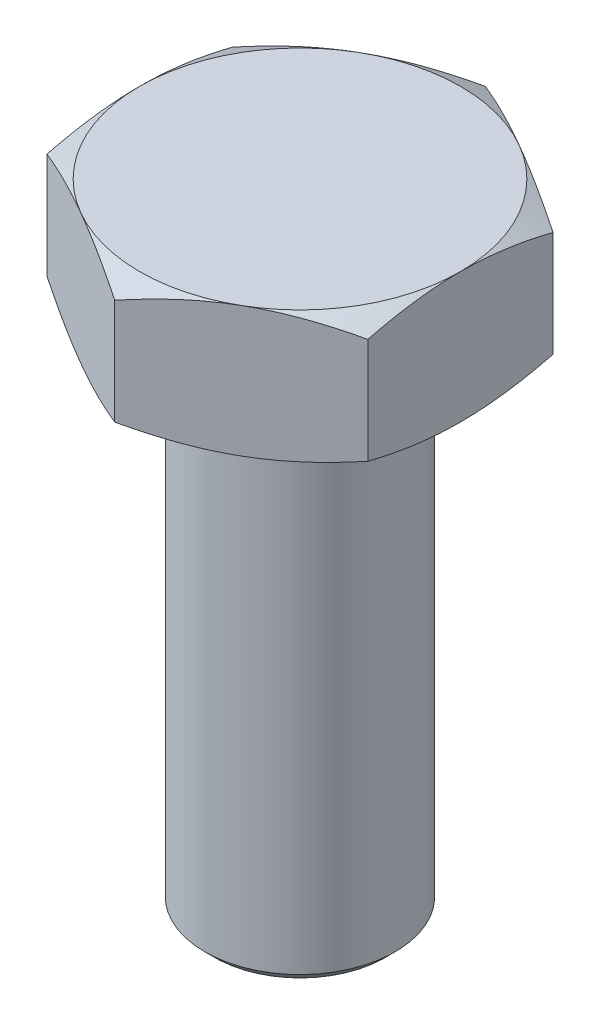
SolidWorks part; units mm, degrees
ref_plane "Front" through (0, 0, 0) normal (0, 0, 1) x (1, 0, 0)
ref_plane "Top" through (0, 0, 0) normal (0, 1, 0) x (1, 0, 0)
ref_plane "Right" through (0, 0, 0) normal (1, 0, 0) x (0, 0, -1)
sketch "Sketch1" plane through (0, 0, 0) normal (0, 1, 0) x (1, 0, 0)
  line L0 (0, 0) -> (0, 9.2376) construction
  line L1 (0, 9.2376) -> (-8, 4.6188)
  line L2 (-8, 4.6188) -> (-8, -4.6188)
  line L3 (-8, -4.6188) -> (0, -9.2376)
  line L4 (0, -9.2376) -> (8, -4.6188)
  line L5 (8, -4.6188) -> (8, 4.6188)
  line L6 (8, 4.6188) -> (0, 9.2376)
  circle A0 centre (0, 0) radius 8 construction
  dimension "D1" = 16
extrude "Boss-Extrude1" add sketch "Sketch1" against normal blind 6.5
sketch "Sketch2" plane through (0, 0, 0) normal (0, 0, 1) x (1, 0, 0)
  line L0 (-11, -1.5) -> (-8, 0)
  line L1 (-8, 0) -> (-8, 1)
  line L2 (-8, 1) -> (-11, 1)
  line L3 (-11, 1) -> (-11, -1.5)
  line L4 (-8, 0) -> (0, 0) construction
  dimension "D1" = 8
  dimension "D2" = 1
  dimension "D3" = 1.5
  dimension "D4" = 3
ref_axis "Axis1" through (0, 50, 0) along (0, -1, 0)
revolve "Cut-Revolve1" cut sketch "Sketch2" angle 360 about axis through (0, 50, 0) along (0, -1, 0)
sketch "Sketch3" plane through (0, -6.5, 0) normal (0, -1, 0) x (1, 0, 0)
  circle A0 centre (0, 0) radius 4.75
  dimension "D1" = 9.5
extrude "Boss-Extrude2" add sketch "Sketch3" along normal blind 25
chamfer "Chamfer1" distance 0.5 angle 45 1 edges at (0, -31.5, -4.75)
ref_plane "Plane1" through (0, -3.25, 0) normal (0, -1, 0) x (-1, 0, 0)
mirror "Mirror1" about plane through (0, -3.25, 0) normal (0, -1, 0) of "Cut-Revolve1"
chamfer "Chamfer2" distance 0.3 angle 45 1 edges at (0, -6.5, -4.75)
